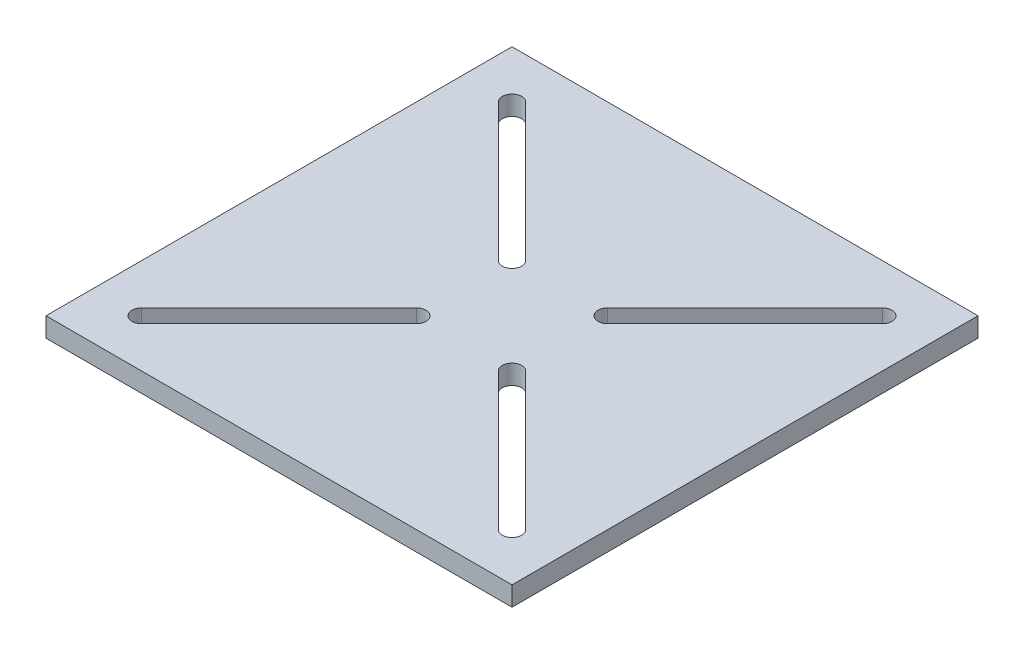
SolidWorks part; units mm, degrees
material "2024-T3"
ref_plane "Front Plane" through (0, 0, 0) normal (0, 0, 1) x (1, 0, 0)
ref_plane "Top Plane" through (0, 0, 0) normal (0, 1, 0) x (1, 0, 0)
ref_plane "Right Plane" through (0, 0, 0) normal (1, 0, 0) x (0, 0, -1)
sketch "Sketch1" plane through (0, 0, 0) normal (0, 1, 0) x (1, 0, 0)
  line L0 (0, 152.4) -> (152.4, 0) construction
  line L1 (0, 0) -> (152.4, 0)
  line L2 (0, 0) -> (0, 152.4)
  line L3 (0, 152.4) -> (152.4, 152.4)
  line L4 (152.4, 0) -> (152.4, 152.4)
  line L5 (76.2, 152.4) -> (76.2, 0) construction
  line L6 (136.7506, 136.7506) -> (91.8494, 91.8494) construction
  line L7 (15.6494, 136.7506) -> (60.5506, 91.8494) construction
  line L8 (17.8944, 138.9957) -> (62.7957, 94.0944)
  line L9 (13.4043, 134.5056) -> (58.3056, 89.6043)
  line L10 (0, 76.2) -> (152.4, 76.2) construction
  line L11 (134.5056, 138.9957) -> (89.6043, 94.0944)
  line L12 (138.9957, 134.5056) -> (94.0944, 89.6043)
  line L13 (136.7506, 15.6494) -> (91.8494, 60.5506) construction
  line L14 (134.5056, 13.4043) -> (89.6043, 58.3056)
  line L15 (138.9957, 17.8944) -> (94.0944, 62.7957)
  line L16 (15.6494, 15.6494) -> (60.5506, 60.5506) construction
  line L17 (17.8944, 13.4043) -> (62.7957, 58.3056)
  line L18 (13.4043, 17.8944) -> (58.3056, 62.7957)
  arc A0 (134.5056, 138.9957) -> (138.9957, 134.5056) centre (136.7506, 136.7506) cw
  arc A1 (94.0944, 89.6043) -> (89.6043, 94.0944) centre (91.8494, 91.8494) cw
  arc A2 (17.8944, 138.9957) -> (13.4043, 134.5056) centre (15.6494, 136.7506) ccw
  arc A3 (58.3056, 89.6043) -> (62.7957, 94.0944) centre (60.5506, 91.8494) ccw
  arc A4 (134.5056, 13.4043) -> (138.9957, 17.8944) centre (136.7506, 15.6494) ccw
  arc A5 (94.0944, 62.7957) -> (89.6043, 58.3056) centre (91.8494, 60.5506) ccw
  arc A6 (17.8944, 13.4043) -> (13.4043, 17.8944) centre (15.6494, 15.6494) cw
  arc A7 (58.3056, 62.7957) -> (62.7957, 58.3056) centre (60.5506, 60.5506) cw
  point P5 (76.2, 76.2)
  point P10 (114.3, 114.3)
  point P12 (38.1, 114.3)
  point P26 (114.3, 38.1)
  point P33 (38.1, 38.1)
  dimension "D2" = 3.175
  dimension "D1" = 152.4
  dimension "D3" = 63.5
  dimension "D4" = 38.1
extrude "Boss-Extrude1" add sketch "Sketch1" along normal blind 6.35
